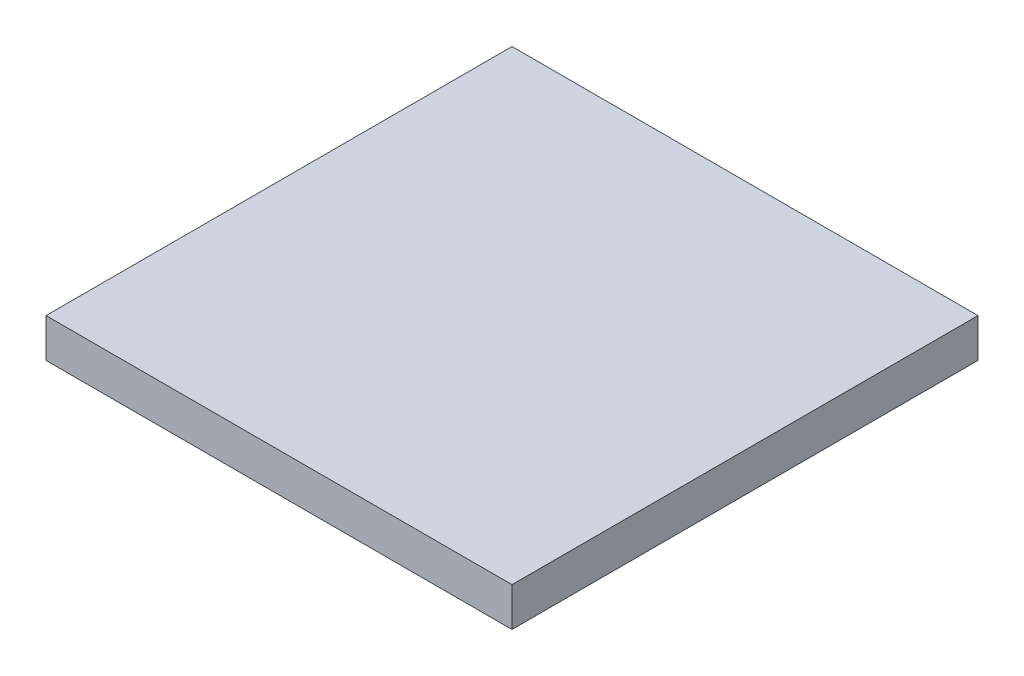
SolidWorks part; units mm, degrees
ref_plane "前视基准面" through (0, 0, 0) normal (0, 0, 1) x (1, 0, 0)
ref_plane "上视基准面" through (0, 0, 0) normal (0, 1, 0) x (1, 0, 0)
ref_plane "右视基准面" through (0, 0, 0) normal (1, 0, 0) x (0, 0, -1)
sketch "草图1" plane through (0, 0, 0) normal (0, 1, 0) x (1, 0, 0)
  line L1 (-3.2136, 2.6471) -> (2.7864, 2.6471)
  line L2 (-3.2136, 2.6471) -> (-3.2136, -3.3529)
  line L3 (-3.2136, -3.3529) -> (2.7864, -3.3529)
  line L4 (2.7864, 2.6471) -> (2.7864, -3.3529)
  dimension "D1" = 6
  dimension "D2" = 6
extrude "凸台-拉伸2" add sketch "草图1" along normal blind 0.5
